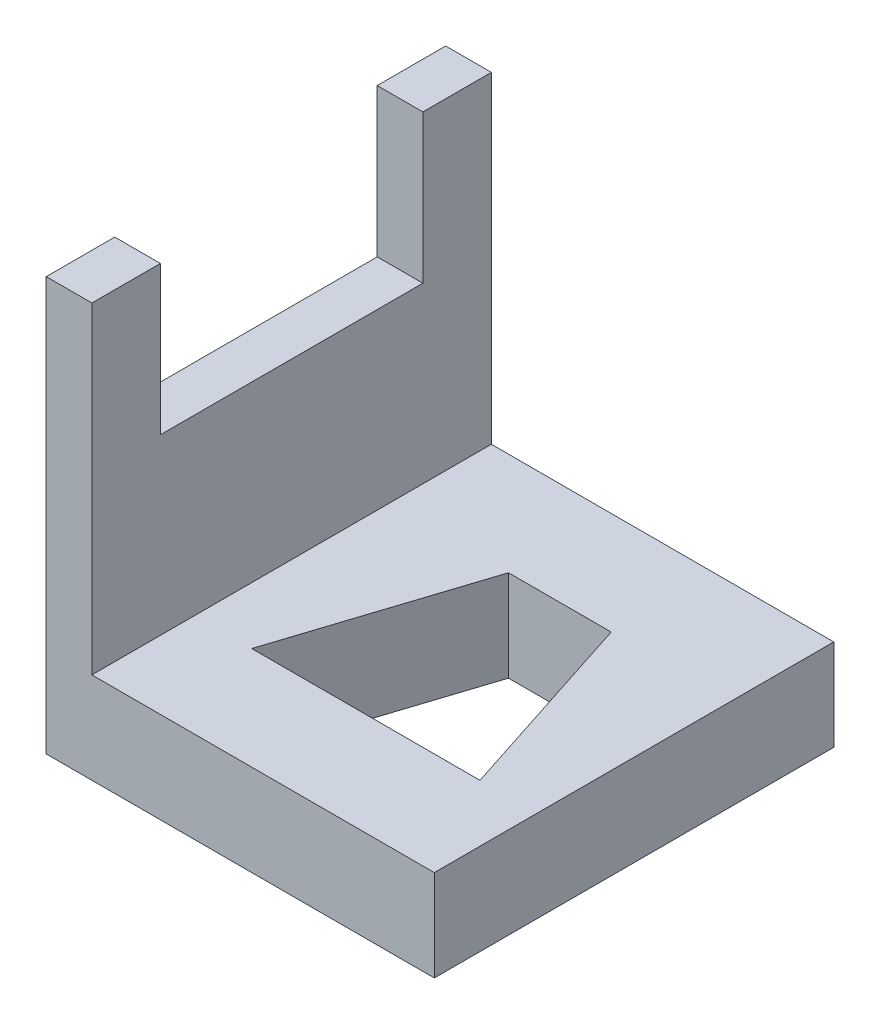
SolidWorks part; units mm, degrees
ref_plane "Ön Düzlem" through (0, 0, 0) normal (0, 0, 1) x (1, 0, 0)
ref_plane "Üst Düzlem" through (0, 0, 0) normal (0, 1, 0) x (1, 0, 0)
ref_plane "Sağ Düzlem" through (0, 0, 0) normal (1, 0, 0) x (0, 0, -1)
sketch "Çizim1" plane through (0, 0, 0) normal (0, 0, 1) x (1, 0, 0)
  line L0 (-3680.581, 1222.866) -> (-3680.581, -617.1065)
  line L1 (-3680.581, -617.1065) -> (-1953.381, -617.1065)
  line L2 (-1953.381, -617.1065) -> (-1953.381, -210.7065)
  line L3 (-1953.381, -210.7065) -> (-3477.381, -210.7065)
  line L4 (-3477.381, -210.7065) -> (-3477.381, 1222.866)
  line L5 (-3477.381, 1222.866) -> (-3680.581, 1222.866)
  dimension "D1" = 1727.2
  dimension "D2" = 1839.9725
  dimension "D3" = 406.4
  dimension "D4" = 203.2
extrude "Yükseklik-Ekstrüzyon1" add sketch "Çizim1" along normal blind 1778
sketch "Çizim3" plane through (-3680.581, 0, 0) normal (-1, 0, 0) x (0, 0, 1)
  line L0 (1778, 1222.866) -> (0, 1222.866) construction
  line L1 (304.8, 1222.866) -> (1473.2, 1222.866)
  line L2 (304.8, 1222.866) -> (304.8, 562.466)
  line L3 (304.8, 562.466) -> (1473.2, 562.466)
  line L4 (1473.2, 1222.866) -> (1473.2, 562.466)
  line L5 (0, 1222.866) -> (0, -617.1065) construction
  dimension "D1" = 1168.4
  dimension "D2" = 304.8
  dimension "D3" = 660.4
extrude "Kes-Ekstrüzyon1" cut sketch "Çizim3" against normal blind 203.2
sketch "Çizim4" plane through (0, -210.7065, 0) normal (0, 1, 0) x (1, 0, 0)
  line L6 (-3477.381, -1778) -> (-3477.381, 0) construction
  line L7 (-2943.981, -457.2) -> (-2486.781, -457.2)
  line L9 (-3223.381, -1320.8) -> (-2207.381, -1320.8)
  line L14 (-2943.981, -457.2) -> (-3223.381, -1320.8)
  line L15 (-2486.781, -457.2) -> (-2207.381, -1320.8)
  line L16 (-1953.381, 0) -> (-3477.381, 0) construction
  dimension "D1" = 1016
  dimension "D2" = 254
  dimension "D3" = 863.6
  dimension "D6" = 457.2
extrude "Kes-Ekstrüzyon2" cut sketch "Çizim4" against normal blind 406.4
